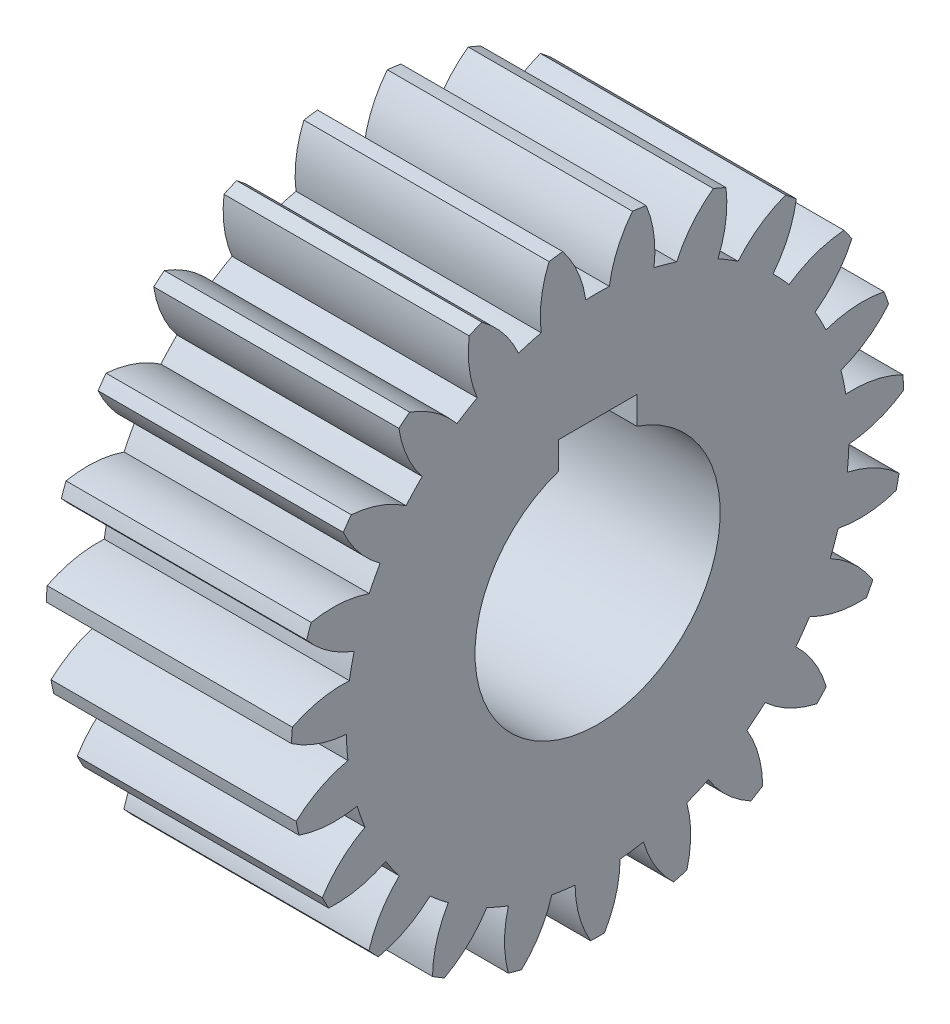
SolidWorks part; units mm, degrees
ref_plane "Plane1" through (0, 0, 0) normal (0, 0, 1) x (1, 0, 0)
ref_plane "Plane2" through (0, 0, 0) normal (0, 1, 0) x (1, 0, 0)
ref_plane "Plane3" through (0, 0, 0) normal (1, 0, 0) x (0, 0, -1)
sketch "HoldingSke" plane through (0, 0, 0) normal (0, 1, 0) x (1, 0, 0)
  line L0 (0, 0) -> (0.1841, -0.0781)
  line L1 (-15, 0) -> (100, 0) construction
  line L2 (0, 0) -> (-2.1039, 2.3779)
  line L3 (0, 0) -> (-11.863, 4.5341)
  line L4 (0, 0) -> (7.9495, 3.3744)
  line L5 (0, 0) -> (-46.8476, -17.4728)
  line L6 (0, 0) -> (-41.4481, -27.9652)
  line L7 (-2.1039, 2.3779) -> (8.6586, 51.2059)
  line L8 (-76.2, 54.61) -> (-71.9, 54.61)
  line L9 (-71.009, 38.7566) -> (-53.1078, 45.2721)
  line L10 (-76.2, 71.12) -> (104.1128, 71.12)
  line L11 (0, 0) -> (-50, 0)
  line L12 (-76.2, 101.6) -> (-76.033, 101.6)
  line L13 (24.9733, 27.94) -> (52.9518, 28.4284)
  line L14 (24.9733, 27.94) -> (24.9743, 27.94)
  line L15 (24.9733, 27.94) -> (100.4006, 29.5858)
  line L16 (-63.627, -5) -> (-12.827, -5)
  circle A0 centre (0, 0) radius 25
  circle A1 centre (0, 0) radius 37.5
  circle A2 centre (0, 0) radius 37.5
  circle A3 centre (0, 0) radius 25
  dimension "MHD" = 75
  dimension "Hub_dia" = 75
  dimension "Bore" = 50
  dimension "MBD" = 50
  dimension "Num_teeth" = 23
  dimension "Pitch" = 0.2
  dimension "Overall_len" = 50
  dimension "Show_teeth" = 23
  dimension "Thickness" = 50
  dimension "OAL" = 50.0001
  dimension "T_dim" = 4.3
  dimension "Ap" = 20
  dimension "H" = 19.05
  dimension "Pitch_radius" = 180.3128
  dimension "Width" = 50
  dimension "Backlash" = 0.167
  dimension "Addendum_fac" = 1
  dimension "Dedendum_fac" = 1.25
  dimension "Clearance_fac" = 0.25
  dimension "Dedendum_add" = 0.001
  dimension "Module" = 5
sketch "BasProSke" plane through (0, 0, 0) normal (0, 1, 0) x (1, 0, 0)
  line L0 (-10, 0) -> (60, 0) construction
  line L1 (0, 0) -> (0, 62.5)
  line L2 (0, 0) -> (50, 0)
  line L3 (50, 0) -> (50, 62.5)
  line L4 (50, 62.5) -> (0, 62.5)
  dimension "Thickness" = 50
  dimension "Diameter" = 125
revolve "Base-Revolve" add sketch "BasProSke" angle 360 about L0
sketch "TooCutSke" plane through (0, 0, 0) normal (1, 0, 0) x (0, 0, -1)
  line L1 (0, 0) -> (0, 107) construction
  line L2 (0, 0) -> (-4.2161, 57.3452) construction
  line L3 (0, 0) -> (-15.6279, 113.7014) construction
  line L4 (-4.2161, 57.3452) -> (-7.8139, 56.8507) construction
  arc A0 (2.4001, 51.1928) -> (-2.4001, 51.1928) centre (0, 0) ccw
  arc A1 (7.134, 62.1171) -> (-7.134, 62.1171) centre (0, 0) ccw
  circle A2 centre (0, 0) radius 57.5 construction
  circle A3 centre (0, 0) radius 54.0323 construction
  arc A4 (-2.4001, 51.1928) -> (-7.134, 62.1171) centre (-25.1516, 47.8214) ccw
  arc A5 (7.134, 62.1171) -> (2.4001, 51.1928) centre (25.1516, 47.8214) ccw
  dimension "Root_dia" = 102.498
  dimension "Overcut_dia" = 125.0508
  dimension "Pitch_dia" = 115
  dimension "Base_dia" = 108.0647
  dimension "Flank_rad" = 23
  dimension "Half_ang" = 7.826
  dimension "Half_CT" = 3.6317
extrude "ToothCut" cut sketch "TooCutSke" along normal through all
fillet "Breaks" [suppressed] radius 0.1
fillet "RootFillets" [suppressed] radius 1.251
pattern_circular "TeethCuts" count 23 every 15.652 about axis through (-10, 0, 0) along (1, 0, 0) of "ToothCut", "RootFillets", "Breaks"
sketch "HubNeaOneSke" plane through (0, 0, 0) normal (-1, 0, 0) x (0, 0, 1)
  circle A0 centre (0, 0) radius 37.5
  dimension "Diameter" = 75
extrude "HubNearOne" [suppressed] add sketch "HubNeaOneSke" along normal blind 12.7001
sketch "HubNeaBotSke" plane through (0, 0, 0) normal (-1, 0, 0) x (0, 0, 1)
  circle A0 centre (0, 0) radius 37.5
  dimension "Diameter" = 75
extrude "HubNearBoth" [suppressed] add sketch "HubNeaBotSke" along normal blind 6.35
ref_plane "FarPln" through (50, 0, 0) normal (1, 0, 0) x (0, 0, -1)
sketch "HubFarSke" plane through (50, 0, 0) normal (1, 0, 0) x (0, 0, -1)
  circle A0 centre (0, 0) radius 37.5
  dimension "Diameter" = 75
extrude "HubFar" [suppressed] add sketch "HubFarSke" along normal blind 6.35
sketch "BorSke" plane through (0, 0, 0) normal (1, 0, 0) x (0, 0, -1)
  circle A0 centre (0, 0) radius 25
  dimension "Diameter" = 50
extrude "Bore" cut sketch "BorSke" along normal mid plane 100.0001
sketch "KeySke" plane through (0, 0, 0) normal (1, 0, 0) x (0, 0, -1)
  line L0 (-8, 0) -> (-8, 29.3)
  line L1 (-8, 29.3) -> (8, 29.3)
  line L2 (8, 29.3) -> (8, 0)
  line L3 (0, 0) -> (0, 34) construction
  line L4 (-8, 0) -> (8, 0)
  dimension "Offset" = 29.3
  dimension "Width" = 16
extrude "Keyway" cut sketch "KeySke" along normal mid plane 100.0001
pattern_circular "Keyway2" [suppressed] count 2 every 90 about axis through (-10, 0, 0) along (1, 0, 0)
equation "' \"Module@HoldingSke\" = 6.35"
equation "' \"Num_teeth@HoldingSke\" = 12"
equation "' \"Ap@HoldingSke\" =  20"
equation "' \"Ap@HoldingSke\" = 20"
equation "' \"Width@HoldingSke\" = 0.5 * 25.4"
equation "' \"Hub_dia@HoldingSke\"= 1 * 25.4"
equation "' \"Hub_dia@HoldingSke\" = 1 * 25.4"
equation "' \"Overall_len@HoldingSke\" = 1.0 * 25.4"
equation "' \"Bore@HoldingSke\" = 0.75 * 25.4"
equation "' \"T_dim@HoldingSke\" = 0.1 * 25.4"
equation "' \"Width@KeySke\" = 0.25 * 25.4"
equation "' \"Show_teeth@HoldingSke\" = 13"
equation "' \"Backlash@HoldingSke\" = 0.009 * 25.4"
equation "' \"Addendum_fac@HoldingSke\" = 1.0"
equation "' \"Dedendum_fac@HoldingSke\" = 1.25"
equation "' \"Dedendum_add@HoldingSke\" = 0.00005 * 25.4"
equation "' \"Clearance_fac@HoldingSke\" = 0.25"
equation "\"Pitch@HoldingSke\" = 1 / \"Module@HoldingSke\""
equation "\"Overcut_dia@TooCutSke\" = (\"Num_teeth@HoldingSke\" + 2 * \"Addendum_fac@HoldingSke\") / \"Pitch@HoldingSke\" + 0.002 * 25.4"
equation "\"Pitch_dia@TooCutSke\" = \"Num_teeth@HoldingSke\" / \"Pitch@HoldingSke\""
equation "\"Base_dia@TooCutSke\" = \"Num_teeth@HoldingSke\" / \"Pitch@HoldingSke\" * cos((\"Ap@HoldingSke\"  * 3.14159265 / 180))"
equation "\"Root_dia@TooCutSke\" = (\"Num_teeth@HoldingSke\" + 2) / \"Pitch@HoldingSke\" - 2 * (\"Addendum_fac@HoldingSke\" + \"Dedendum_fac@HoldingSke\") / \"Pitch@HoldingSke\" - \"Dedendum_add@HoldingSke\" * 2"
equation "\"Half_ang@TooCutSke\" = 180 / \"Num_teeth@HoldingSke\""
equation "\"Half_CT@TooCutSke\" = \"Num_teeth@HoldingSke\" / \"Pitch@HoldingSke\" * sin((3.14159265 / 2 / \"Num_teeth@HoldingSke\")) / 2 - 7 * \"Backlash@HoldingSke\" / 4"
equation "\"Flank_rad@TooCutSke\" = \"Num_teeth@HoldingSke\" / \"Pitch@HoldingSke\" / 5"
equation "\"Radius@RootFillets\" = \"Clearance_fac@HoldingSke\" / \"Pitch@HoldingSke\" + \"Dedendum_add@HoldingSke\""
equation "\"Break_rad@Breaks\" = 0.02 / \"Pitch@HoldingSke\""
equation "\"Thickness@HoldingSke\" = \"Width@HoldingSke\""
equation "\"OAL@HoldingSke\" = \"Thickness@HoldingSke\""
equation "\"MHD@HoldingSke\" = (\"Num_teeth@HoldingSke\" + 2) / \"Pitch@HoldingSke\" - 2 * (\"Addendum_fac@HoldingSke\" + \"Dedendum_fac@HoldingSke\")  / \"Pitch@HoldingSke\" - \"Dedendum_add@HoldingSke\" * 2"
equation "\"MBD@HoldingSke\" = (\"Num_teeth@HoldingSke\" + 2) / \"Pitch@HoldingSke\" - 2 * (\"Addendum_fac@HoldingSke\" + \"Dedendum_fac@HoldingSke\")  / \"Pitch@HoldingSke\" - \"Dedendum_add@HoldingSke\" * 2 - 0.002 * 25.4"
equation "\"MHD@HoldingSke\" = ((sgn( \"MHD@HoldingSke\" - \"Hub_dia@HoldingSke\" )-1)*( \"MHD@HoldingSke\" - \"Hub_dia@HoldingSke\" ))/-2+ \"Hub_dia@HoldingSke\""
equation "\"MBD@HoldingSke\" = ((sgn( \"MBD@HoldingSke\" - \"Bore@HoldingSke\" )-1)*( \"MBD@HoldingSke\" - \"Bore@HoldingSke\" ))/-2+ \"Bore@HoldingSke\""
equation "\"OAL@HoldingSke\" = ((sgn( \"OAL@HoldingSke\" - \"Overall_len@HoldingSke\" )+1)*( \"OAL@HoldingSke\" - \"Overall_len@HoldingSke\" ))/2 + \"Overall_len@HoldingSke\" + 0.000002 * 25.4"
equation "\"Num_teeth@TeethCuts\" = int( \"Show_teeth@HoldingSke\" ) + 1"
equation "\"Num_teeth@TeethCuts\" = ((sgn( \"Num_teeth@TeethCuts\" - \"Num_teeth@HoldingSke\" )-1)*( \"Num_teeth@TeethCuts\" - \"Num_teeth@HoldingSke\" ))/-2+ \"Num_teeth@HoldingSke\""
equation "\"Num_teeth@TeethCuts\" = ((sgn( \"Num_teeth@TeethCuts\" - 2.0)+1)*( \"Num_teeth@TeethCuts\" - 2.0))/2 +2.0"
equation "\"Angle@TeethCuts\" = 360.0 / \"Num_teeth@HoldingSke\""
equation "\"Diameter@BasProSke\" = (\"Num_teeth@HoldingSke\" + 2 * \"Addendum_fac@HoldingSke\") / \"Pitch@HoldingSke\""
equation "\"Thickness@BasProSke\"  = \"Thickness@HoldingSke\""
equation "' \"Fillet_rad@BasProSke\" =  \"Thickness@HoldingSke\" * 0.05"
equation "' \"Fillet_rad@BasProSke\" = \"Thickness@HoldingSke\" * 0.05"
equation "\"MHD@HoldingSke\" = ((sgn( \"MHD@HoldingSke\" - \"Root_dia@TooCutSke\" )-1)*( \"MHD@HoldingSke\" - \"Root_dia@TooCutSke\" ))/-2+ \"Root_dia@TooCutSke\""
equation "\"Diameter@HubNeaOneSke\" = \"MHD@HoldingSke\""
equation "\"Length@HubNearOne\" = \"OAL@HoldingSke\" - \"Thickness@BasProSke\""
equation "\"Diameter@HubNeaBotSke\" = \"MHD@HoldingSke\""
equation "\"Length@HubNearBoth\" = ( \"OAL@HoldingSke\" - \"Thickness@BasProSke\" ) / 2.0"
equation "\"Thickness@FarPln\" = \"Thickness@BasProSke\""
equation "\"Diameter@HubFarSke\" = \"MHD@HoldingSke\""
equation "\"Length@HubFar\" = ( \"OAL@HoldingSke\" - \"Thickness@BasProSke\" ) / 2.0"
equation "\"Diameter@BorSke\" = \"MBD@HoldingSke\""
equation "\"D1@Bore\" = \"OAL@HoldingSke\" * 2.0"
equation "\"D1@Keyway\" = \"OAL@HoldingSke\" * 2.0"
equation "\"Offset@KeySke\" = \"T_dim@HoldingSke\" + \"MBD@HoldingSke\" / 2.0"
